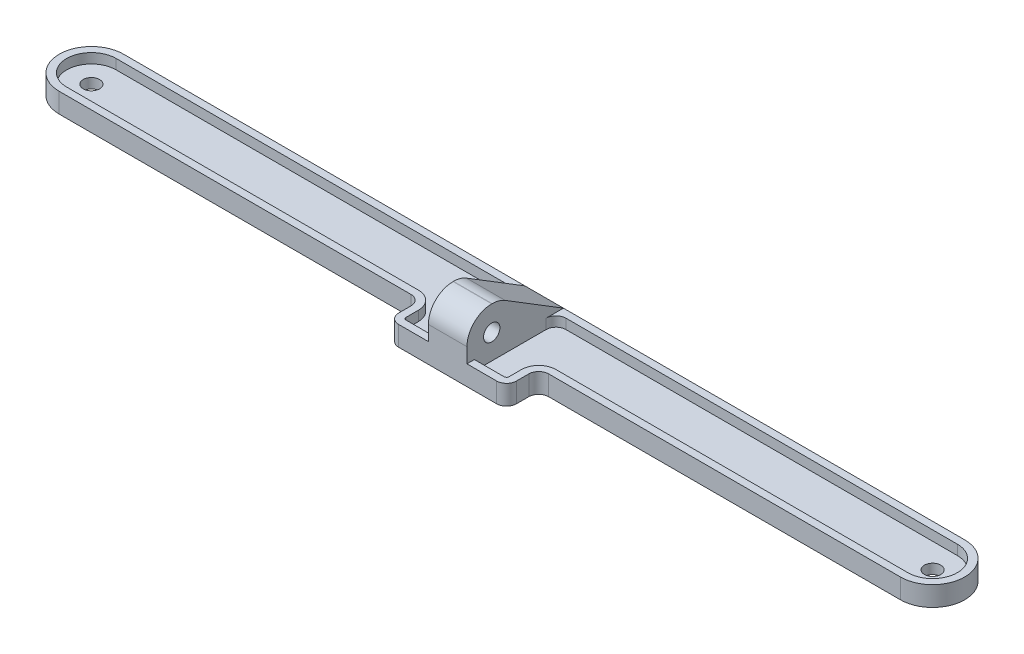
SolidWorks part; units mm, degrees
ref_plane "Front Plane" through (0, 0, 0) normal (0, 0, 1) x (1, 0, 0)
ref_plane "Top Plane" through (0, 0, 0) normal (0, 1, 0) x (1, 0, 0)
ref_plane "Right Plane" through (0, 0, 0) normal (1, 0, 0) x (0, 0, -1)
sketch "Sketch1" plane through (0, 0, 0) normal (0, 1, 0) x (1, 0, 0)
  line L0 (-85, 0) -> (85, 0)
  line L1 (-85, 0) -> (85, 0) construction
  line L2 (-85, 6.5) -> (85, 6.5)
  line L3 (-85, -6.5) -> (85, -6.5)
  circle A0 centre (-85, 0) radius 1.65
  circle A1 centre (85, 0) radius 1.65
  arc A2 (-85, 6.5) -> (-85, -6.5) centre (-85, 0) ccw
  arc A3 (85, -6.5) -> (85, 6.5) centre (85, 0) ccw
  point P4 (0, 0)
  point P8 (0, 0)
  dimension "D2" = 3.3
  dimension "D1" = 170
  dimension "D3" = 13
extrude "Boss-Extrude1" add sketch "Sketch1" along normal mid plane 2
sketch "Sketch2" plane through (0, 1, 0) normal (0, 1, 0) x (1, 0, 0)
  line L0 (-85, 6.5) -> (85, 6.5) construction
  line L1 (-3.9, -6.5) -> (3.9, -6.5)
  line L2 (-3.9, -6.5) -> (-3.9, 6.5)
  line L3 (-3.9, 6.5) -> (3.9, 6.5)
  line L4 (3.9, -6.5) -> (3.9, 6.5)
  line L5 (-3.9, -6.5) -> (3.9, 6.5) construction
  line L6 (-3.9, 6.5) -> (3.9, -6.5) construction
  point P0 (0, 0)
  dimension "D1" = 7.8
extrude "Boss-Extrude2" add sketch "Sketch2" along normal blind 10
sketch "Sketch3" plane through (3.9, 0, 0) normal (1, 0, 0) x (0, 0, -1)
  line L0 (-6.5, 11) -> (-8, 11)
  line L2 (-13, 6) -> (-13, -1)
  line L3 (-13, -1) -> (-6.5, -1)
  line L4 (-6.5, -1) -> (-6.5, 11)
  line L5 (-6.5, 1) -> (6.5, 1) construction
  arc A1 (-8, 11) -> (-13, 6) centre (-8, 6) ccw
  point P2 (-6.5, 11)
  point P5 (-6.5, 1)
  point P8 (-8, 11)
  point P12 (0, 1)
  line M5 (-6.5, 11) -> (-6.5, 1)
  dimension "D1" = 10
  dimension "D2" = 8
extrude "Boss-Extrude3" add sketch "Sketch3" against normal up to surface (7.8 mm away) contours A1 L2 L3 L4 | A1 L0 M5 | A1 up to face at (-3.9, 6, 0)
sketch "Sketch4" plane through (3.9, 0, 0) normal (1, 0, 0) x (0, 0, -1)
  circle A0 centre (-8, 6) radius 1.65
  dimension "D1" = 3.3
extrude "Cut-Extrude1" cut sketch "Sketch4" against normal through all both
sketch "Sketch7" plane through (0, 1, 0) normal (0, 1, 0) x (1, 0, 0)
  line L0 (3.9, -6.5) -> (11.9, -6.5)
  line L1 (3.9, -6.5) -> (85, -6.5) construction
  line L2 (11.9, -6.5) -> (11.9, -13)
  line L3 (11.9, -13) -> (3.9, -13)
  line L4 (3.9, -6.5) -> (3.9, -13)
  line L5 (-11.9, -6.5) -> (-3.9, -6.5)
  line L6 (-85, -6.5) -> (-3.9, -6.5) construction
  line L7 (-3.9, -6.5) -> (-3.9, -13)
  line L8 (-3.9, -13) -> (-11.9, -13)
  line L9 (-11.9, -13) -> (-11.9, -6.5)
  point P13 (0, 0)
  line M10 (3.9, -6.5) -> (85, -6.5)
  dimension "D1" = 8
extrude "Boss-Extrude5" add sketch "Sketch7" against normal up to surface (2 mm away) contours L9 L8 L7 L5 | L4 L3 L2 M10 up to face at (85, -1, 1.65)
fillet "Fillet3" radius 2 4 edges at (-11.9, 0, 6.5) (-11.9, 0, 13) (11.9, 0, 6.5) (11.9, 0, 13)
sketch "Sketch5" plane through (0, 1, 0) normal (0, 1, 0) x (1, 0, 0)
  line L0 (-85, 0) -> (85, 0) construction
  line L1 (-85, 6.5) -> (85, 6.5)
  line L2 (-85, -6.5) -> (-13.9, -6.5)
  line L3 (3.9, 6.5) -> (85, 6.5) construction
  line L6 (11.9, -8.5) -> (11.9, -11) construction
  line L8 (-11.9, -8.5) -> (-11.9, -11)
  line L9 (-9.9, -13) -> (9.9, -13)
  line L10 (11.9, -8.5) -> (11.9, -11)
  line L11 (9.9, -13) -> (3.9, -13) construction
  line L12 (-11.9, -11) -> (-11.9, -8.5) construction
  line L13 (13.9, -6.5) -> (85, -6.5)
  line L14 (-85, 5) -> (85, 5)
  line L15 (13.9, -5) -> (85, -5)
  line L16 (10.4, -8.5) -> (10.4, -11)
  line L17 (-9.9, -11.5) -> (9.9, -11.5)
  line L18 (-10.4, -8.5) -> (-10.4, -11)
  line L19 (-85, -5) -> (-13.9, -5)
  arc A0 (13.9, -6.5) -> (11.9, -8.5) centre (13.9, -8.5) ccw
  arc A1 (-85, 6.5) -> (-85, -6.5) centre (-85, 0) ccw
  arc A2 (85, -6.5) -> (85, 6.5) centre (85, 0) ccw
  circle A5 centre (-85, 0) radius 1.65 construction
  arc A6 (9.9, -13) -> (11.9, -11) centre (9.9, -11) ccw
  arc A7 (-11.9, -11) -> (-9.9, -13) centre (-9.9, -11) ccw
  arc A8 (-13.9, -6.5) -> (-11.9, -8.5) centre (-13.9, -8.5) cw
  arc A9 (85, -5) -> (85, 5) centre (85, 0) ccw
  arc A10 (13.9, -5) -> (10.4, -8.5) centre (13.9, -8.5) ccw
  arc A11 (9.9, -11.5) -> (10.4, -11) centre (9.9, -11) ccw
  arc A12 (-10.4, -11) -> (-9.9, -11.5) centre (-9.9, -11) ccw
  arc A13 (-13.9, -5) -> (-10.4, -8.5) centre (-13.9, -8.5) cw
  arc A14 (-85, 5) -> (-85, -5) centre (-85, 0) ccw
  point P5 (0, 0)
  dimension "D1" = 2
  dimension "D2" = 1.5
extrude "Boss-Extrude4" add sketch "Sketch5" along normal blind 2
sketch "Sketch6" plane through (-3.9, 0, 0) normal (-1, 0, 0) x (0, 0, 1)
  line L0 (8, 11) -> (6.5, 11)
  line L1 (-6.5, 11) -> (8, 11) construction
  line L2 (6.5, 11) -> (-6.5, 3)
  line L3 (-6.5, 3) -> (-6.5, 11)
  line L4 (-6.5, 11) -> (6.5, 11)
  circle A0 centre (8, 6) radius 5 construction
  line M11 (8, 11) -> (-6.5, 11)
  line M12 (-6.5, 11) -> (-6.5, 3)
extrude "Cut-Extrude2" cut sketch "Sketch6" against normal blind 10 contours L2 M11 M12
fillet "Fillet1" radius 5 1 edges at (0, 11, 6.5)
fillet "Fillet2" radius 2 2 edges at (-3.9, 2, -5) (3.9, 2, -5)
